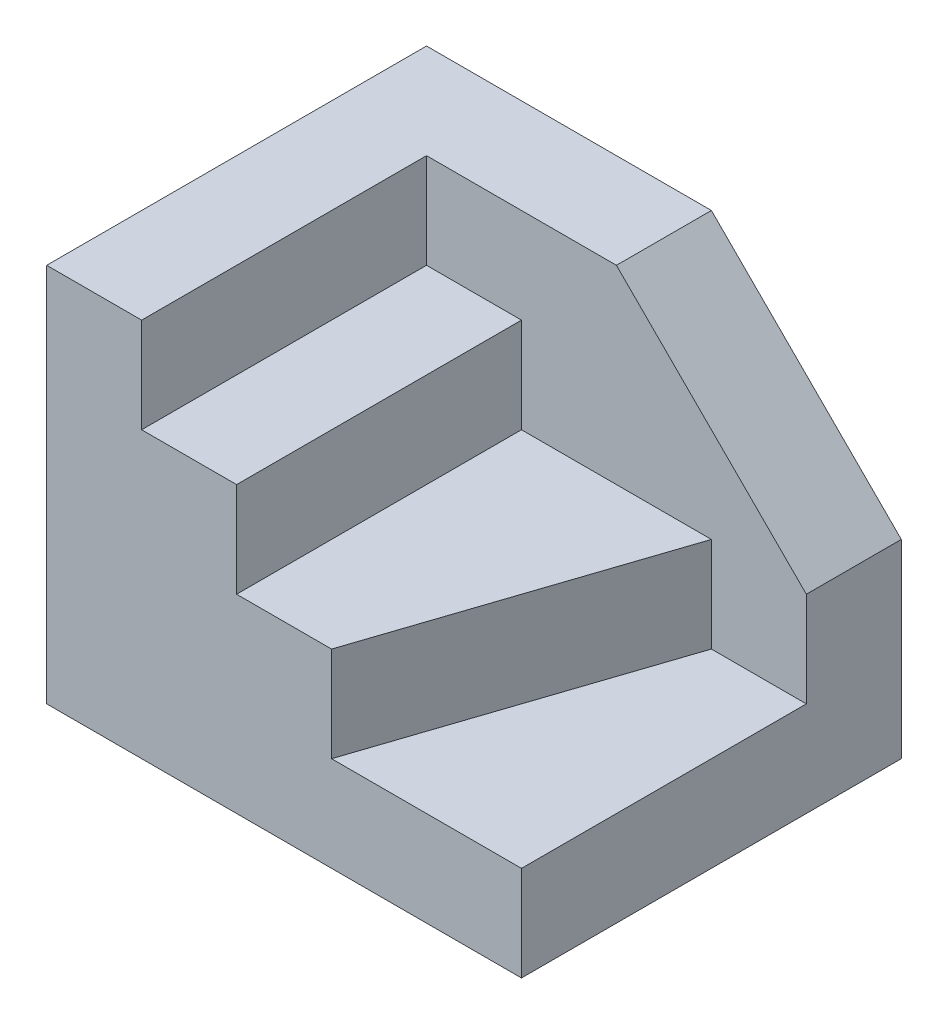
SolidWorks part; units mm, degrees
ref_plane "前基準面" through (0, 0, 0) normal (0, 0, 1) x (1, 0, 0)
ref_plane "上基準面" through (0, 0, 0) normal (0, 1, 0) x (1, 0, 0)
ref_plane "右基準面" through (0, 0, 0) normal (1, 0, 0) x (0, 0, -1)
sketch "草圖1" plane through (0, 0, 0) normal (0, 1, 0) x (1, 0, 0)
  line L1 (0, 0) -> (25, 0)
  line L2 (0, 0) -> (0, -20)
  line L3 (0, -20) -> (25, -20)
  line L4 (25, 0) -> (25, -20)
  dimension "D1" = 25
  dimension "D2" = 20
extrude "填料-伸長1" add sketch "草圖1" along normal blind 5
sketch "草圖2" plane through (0, 5, 0) normal (0, 1, 0) x (1, 0, 0)
  line L0 (0, 0) -> (0, -20) construction
  line L1 (15, 0) -> (0, 0)
  line L2 (25, 0) -> (0, 0) construction
  line L3 (15, -5) -> (0, -5)
  line L4 (0, 0) -> (0, -5)
  line L5 (15, 0) -> (15, -5)
  line L6 (0, -20) -> (5, -20)
  line L7 (0, -20) -> (0, 0)
  line L8 (0, 0) -> (5, 0)
  line L9 (5, -20) -> (5, 0)
  line M6 (0, 0) -> (0, -20)
  line M7 (0, -20) -> (25, -20)
  line M9 (25, 0) -> (0, 0)
  dimension "D1" = 5
  dimension "D2" = 5
  dimension "D3" = 15
extrude "填料-伸長2" add sketch "草圖2" along normal blind 15 contours L9 L3 M7 M6 | L3 L9 L1 M6 | L9 L3 L5 M9
sketch "草圖3" plane through (0, 0, 5) normal (0, 0, 1) x (1, 0, 0)
  line L0 (5, 5) -> (25, 5) construction
  line L1 (15, 20) -> (15, 5) construction
  line L2 (15, 5) -> (25, 5)
  line L3 (15, 20) -> (15, 5)
  line L4 (15, 20) -> (25, 10)
  line L6 (25, 10) -> (25, 5)
  dimension "D1" = 5
extrude "填料-伸長3" add sketch "草圖3" against normal up to surface (5 mm away) up to face at (13.3333, 8.3333, 0)
sketch "草圖4" plane through (0, 0, 20) normal (0, 0, 1) x (1, 0, 0)
  line L1 (5, 5) -> (10, 5)
  line L2 (5, 5) -> (5, 15)
  line L3 (5, 15) -> (10, 15)
  line L4 (10, 5) -> (10, 15)
  dimension "D1" = 5
  dimension "D2" = 10
extrude "填料-伸長4" add sketch "草圖4" against normal up to surface (15 mm away) up to face at (15, 12, 5)
sketch "草圖5" plane through (0, 5, 0) normal (0, 1, 0) x (1, 0, 0)
  line L0 (10, -20) -> (25, -20) construction
  line L1 (25, -5) -> (10, -5) construction
  line L2 (10, -5) -> (10, -20) construction
  line L3 (10, -20) -> (15, -20)
  line L4 (20, -5) -> (10, -5)
  line L5 (10, -5) -> (10, -20)
  line L6 (20, -5) -> (15, -20)
  dimension "D1" = 10
  dimension "D2" = 5
extrude "填料-伸長6" add sketch "草圖5" along normal blind 5 contours L6 L3 L5 L4
